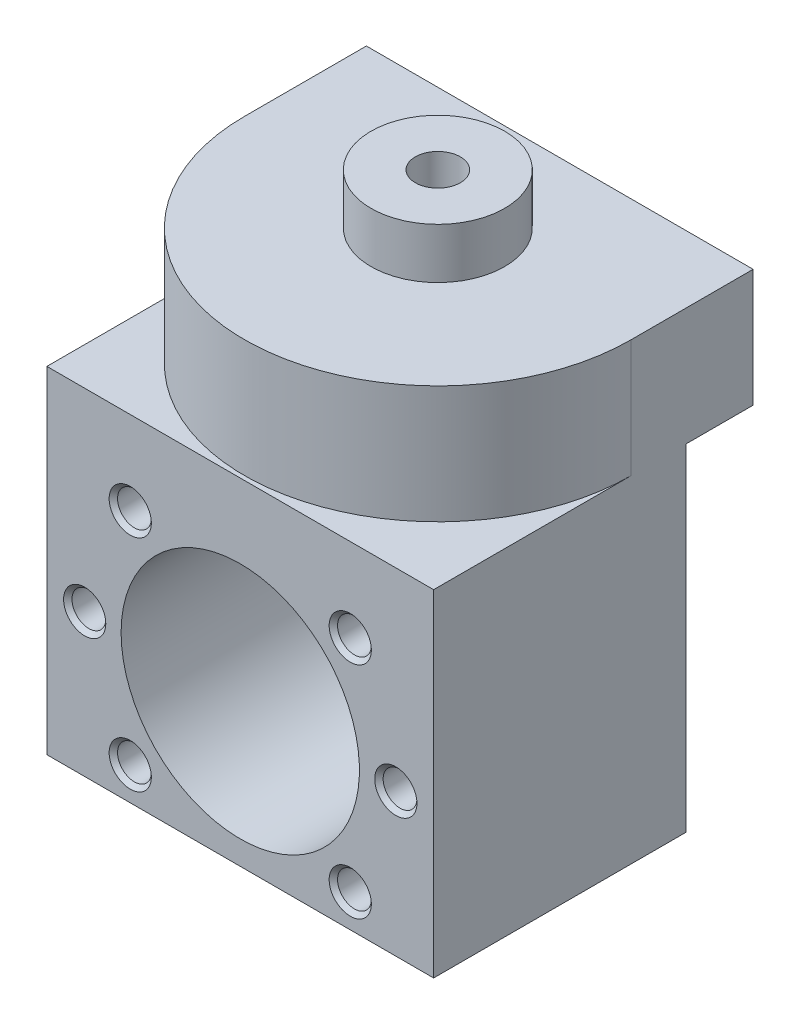
SolidWorks part; units mm, degrees
material "6061-T6 (SS)"
ref_plane "Front Plane" through (0, 0, 0) normal (0, 0, 1) x (1, 0, 0)
ref_plane "Top Plane" through (0, 0, 0) normal (0, 1, 0) x (1, 0, 0)
ref_plane "Right Plane" through (0, 0, 0) normal (1, 0, 0) x (0, 0, -1)
sketch "Sketch1" plane through (0, 0, 0) normal (0, 1, 0) x (1, 0, 0)
  line L1 (-29.21, 19.05) -> (29.21, 19.05)
  line L2 (-29.21, 19.05) -> (-29.21, -19.05)
  line L3 (-29.21, -19.05) -> (29.21, -19.05)
  line L4 (29.21, 19.05) -> (29.21, -19.05)
  line L5 (-29.21, 19.05) -> (29.21, -19.05) construction
  line L6 (-29.21, -19.05) -> (29.21, 19.05) construction
  point P0 (0, 0)
  dimension "D1" = 58.42
  dimension "D2" = 38.1
extrude "Boss-Extrude1" add sketch "Sketch1" along normal blind 50.8
sketch "Sketch2" plane through (0, 50.8, 0) normal (0, 1, 0) x (-1, 0, 0)
  line L0 (-29.21, -19.05) -> (29.21, -19.05) construction
  line L1 (-29.21, 19.05) -> (-29.21, -19.05) construction
  line L2 (29.21, -29.21) -> (29.21, -10.795)
  line L3 (29.21, -19.05) -> (29.21, 19.05) construction
  line L4 (-29.21, -29.21) -> (-29.21, -10.795)
  line L5 (0, -19.05) -> (-25.7429, 3.0081) construction
  line L6 (25.84, 2.8255) -> (0, -19.05) construction
  line L7 (29.21, -29.21) -> (-29.21, -29.21)
  arc A0 (29.21, -10.795) -> (0, 18.415) centre (0, -10.795) ccw
  arc A1 (0, 18.415) -> (-29.21, -10.795) centre (0, -10.795) ccw
  point P0 (0, -19.05)
  dimension "D1" = 10.16
  dimension "D2" = 18.415
extrude "Boss-Extrude3" add sketch "Sketch2" along normal blind 17.78
sketch "Sketch3" plane through (0, 68.58, 0) normal (0, 1, 0) x (-1, 0, 0)
  circle A0 centre (0, -10.795) radius 10.0965
  arc A1 (29.21, -10.795) -> (-29.21, -10.795) centre (0, -10.795) ccw construction
  dimension "D1" = 20.193
extrude "Boss-Extrude4" add sketch "Sketch3" along normal blind 7.62
sketch "Sketch8" plane through (0, 0, -19.05) normal (0, 0, -1) x (-1, 0, 0)
  line L0 (-29.21, 68.58) -> (29.21, 68.58) construction
  circle A0 centre (0, 21.59) radius 18
  dimension "D1" = 36
  dimension "D2" = 46.99
extrude "Cut-Extrude2" cut sketch "Sketch8" against normal through all
hole_wizard "M8x1.25 Tapped Hole1" positions "Sketch5" profile "Sketch4" tap size "M8x1.25" standard "Ansi Metric"
sketch "Sketch5" plane through (0, 76.2, 0) normal (0, 1, 0) x (-1, 0, 0)
  point P1 (0, -10.795)
sketch "Sketch4" plane through (0, 76.2, -10.795) normal (1, 0, 0) x (0, 0, 1)
  line L0 (0, 0) -> (0, 27.4429)
  line L1 (0, 27.4429) -> (3.4, 25.4)
  line L2 (3.4, 25.4) -> (3.4, 0)
  line L5 (3.4, 0) -> (0, 0)
  line L10 (0, 27.4429) -> (-3.4, 25.4) construction
  line L11 (0, -6.35) -> (0, 107.95) construction
  dimension "Tap Drill Dia." = 6.8
  dimension "Tap Drill Depth" = 25.4
  dimension "Drill Angle" = 118
hole_wizard "1/4-20 Tapped Hole1" positions "Sketch14" profile "Sketch13" tap size "1/4-20" standard "ANSI Inch"
sketch "Sketch14" plane through (0, 0, -19.05) normal (0, 0, -1) x (-1, 0, 0)
  circle A0 centre (0, 21.59) radius 23.5
  point P1 (23.5, 21.59)
  dimension "D1" = 47
sketch "Sketch13" plane through (-23.5, 21.59, -19.05) normal (1, 0, 0) x (0, 1, 0)
  line L0 (0, 0) -> (0, 20.5838)
  line L1 (0, 20.5838) -> (2.5527, 19.05)
  line L2 (2.5527, 19.05) -> (2.5527, 0.635)
  line L3 (2.5527, 0.635) -> (3.1877, 0)
  line L5 (3.1877, 0) -> (0, 0)
  line L6 (-2.5527, 0.635) -> (-3.1877, 0) construction
  line L10 (0, 20.5838) -> (-2.5527, 19.05) construction
  line L11 (0, -6.35) -> (0, 107.95) construction
  dimension "Tap Drill Dia." = 5.1054
  dimension "Tap Drill Depth" = 19.05
  dimension "Near C'Sink Dia." = 6.3754
  dimension "Near C'Sink Angle" = 90
  dimension "Drill Angle" = 118
cosmetic thread "Hole Thread2" parameters "D1"=15.24, "D2"=6.35
pattern_circular "CirPattern2" count 8 over 360 about axis through (0, 21.59, 0) along (0, 0, 1) skipping 2, 6 of "1/4-20 Tapped Hole1"
mirror "Mirror2" about plane through (0, 0, 0) normal (0, 0, 1) of "CirPattern2", "1/4-20 Tapped Hole1"
